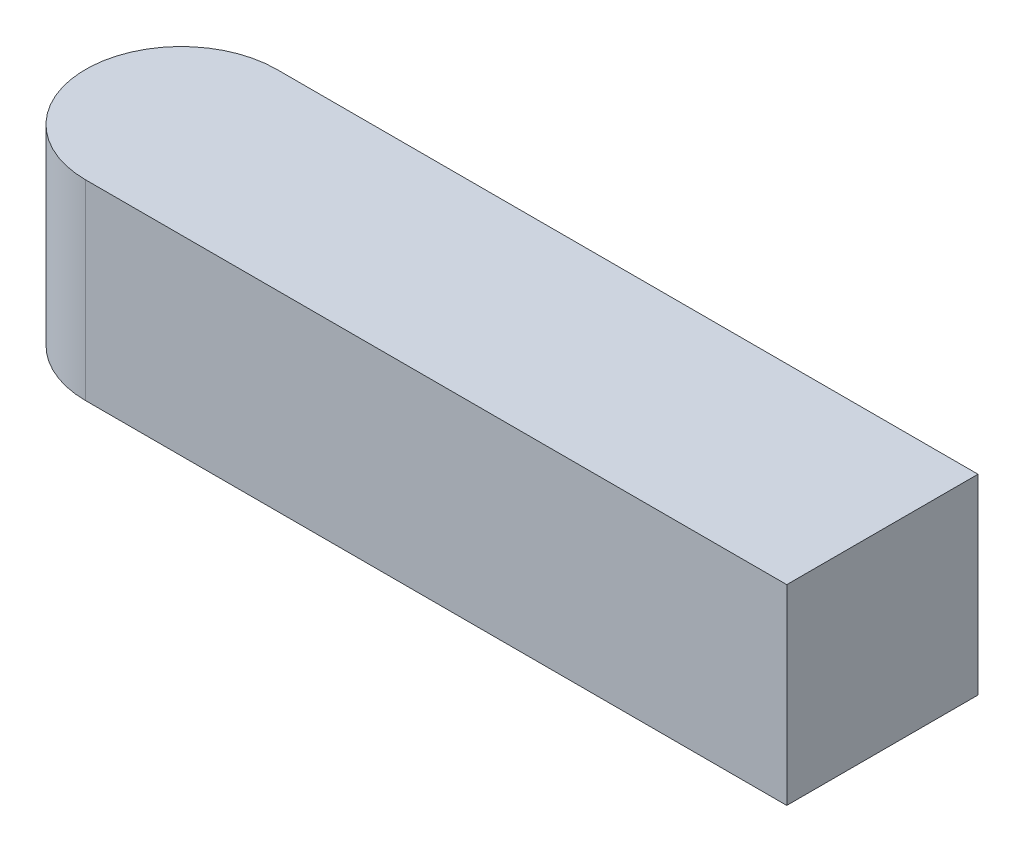
SolidWorks part; units mm, degrees
material "Cast Alloy Steel"
ref_plane "Front Plane" through (0, 0, 0) normal (0, 0, 1) x (1, 0, 0)
ref_plane "Top Plane" through (0, 0, 0) normal (0, 1, 0) x (1, 0, 0)
ref_plane "Right Plane" through (0, 0, 0) normal (1, 0, 0) x (0, 0, -1)
sketch "Sketch1" plane through (0, 0, 0) normal (0, 1, 0) x (1, 0, 0)
  line L0 (-50, 0) -> (50, 0) construction
  line L1 (-44, 0) -> (44, 0) construction
  line L2 (-44, 6) -> (44, 6)
  line L3 (-44, -6) -> (44, -6)
  arc A0 (-44, 6) -> (-44, -6) centre (-44, 0) ccw
  arc A1 (44, -6) -> (44, 6) centre (44, 0) ccw
  point P4 (0, 0)
  point P7 (0, 0)
  dimension "D" = 6
  dimension "L" = 100
extrude "Boss-Extrude1" add sketch "Sketch1" along normal blind 12
sketch "Sketch2" plane through (0, 12, 0) normal (0, 1, 0) x (1, 0, 0)
  line L0 (44, 6) -> (-44, 6) construction
  line L1 (0, 6) -> (50, 6)
  line L2 (0, 6) -> (0, -6)
  line L3 (0, -6) -> (50, -6)
  line L4 (50, 6) -> (50, -6)
  line L5 (-44, -6) -> (44, -6) construction
  arc A0 (44, -6) -> (44, 6) centre (44, 0) ccw construction
extrude "Cut-Extrude1" cut sketch "Sketch2" against normal through all
equation "\"L\"= 100"
equation "\"D\"= 6"
equation "\"H\"= 12"
equation "\"Cut-Extrude1\"= IIF ( \"L\" = 160 , \"unsuppressed\" , IIF ( \"L\" = 100 , \"unsuppressed\" , \"suppressed\" ) )"
equation "\"L@Sketch1\"=\"L\""
equation "\"D@Sketch1\"=\"D\""
equation "\"H@Boss-Extrude1\"=\"H\""
